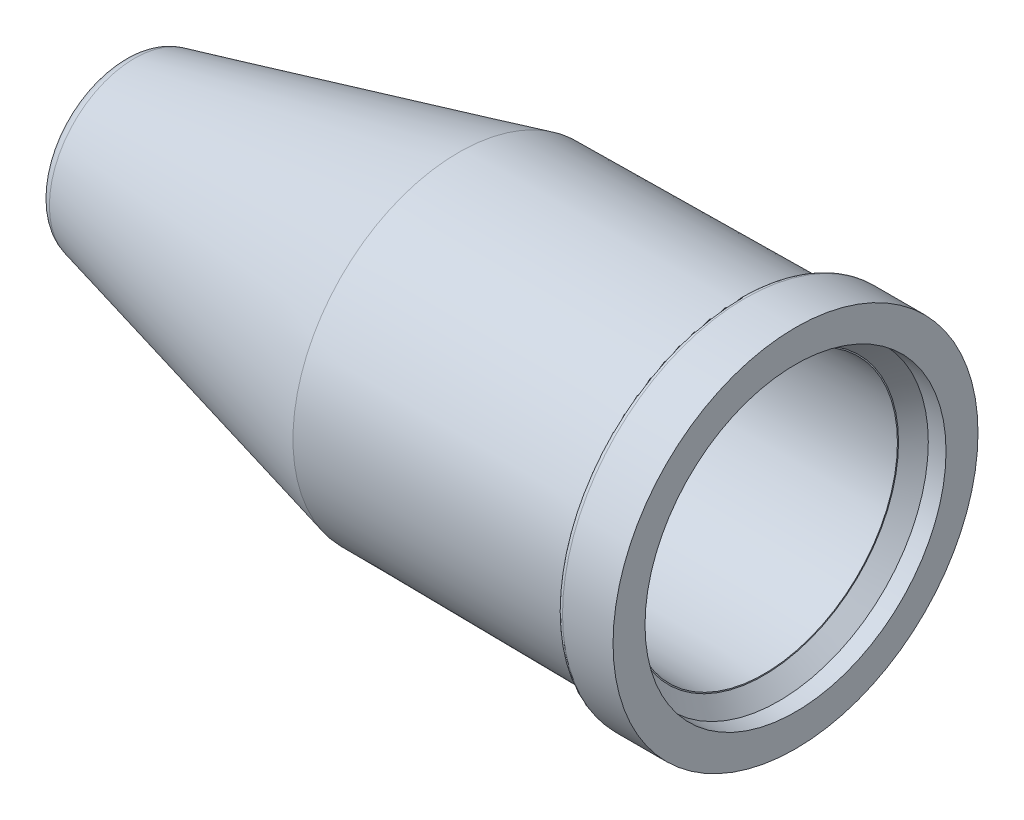
SolidWorks part; units mm, degrees
material "PBT Propósitos gerais"
ref_plane "Frontal" through (0, 0, 0) normal (0, 0, 1) x (1, 0, 0)
ref_plane "Superior" through (0, 0, 0) normal (0, 1, 0) x (1, 0, 0)
ref_plane "Lateral" through (0, 0, 0) normal (1, 0, 0) x (0, 0, -1)
sketch "Sketch1" plane through (0, 0, 0) normal (0, 0, 1) x (1, 0, 0)
  line L0 (3, 0) -> (-11, 0) construction
  line L1 (0, 2.6807) -> (0, 3.25)
  line L2 (0, 3.25) -> (-1, 3.25)
  line L3 (-1, 3.25) -> (-1, 3)
  line L4 (-1, 3) -> (-6, 2.951)
  line L5 (-6, 2.951) -> (-12, 1.46)
  line L6 (-12, 1.46) -> (-12, 1.1823) construction
  line L7 (-11.57, 0.9) -> (-7.9512, 0.8621) construction
  line L8 (-7.8522, 0.7621) -> (-7.8522, 0.4926)
  line L9 (-7.8522, 0.4926) -> (-3.5277, 0.4926)
  line L10 (-9.53, 1.475) -> (-7.28, 1.475)
  line L11 (-7.28, 1.1084) -> (-3.6842, 1.069)
  line L12 (-7.28, 1.1084) -> (-7.28, 1.25)
  line L13 (-7.28, 1.25) -> (-10.3301, 1.25) construction
  line L14 (-0.3, 2.665) -> (-0.565, 2.4)
  line L15 (-12, 1.1823) -> (-11.8522, 1.1823) construction
  line L16 (-6.81, 2.3268) -> (-0.565, 2.38)
  line L17 (-8.0717, 1.9768) -> (-10.3321, 1.35) construction
  line L18 (-10.3321, 1.35) -> (-10.3301, 1.25) construction
  line L19 (-11.8522, 1.1823) -> (-11.57, 0.9) construction
  line L20 (-6.81, 2.3268) -> (-7.5, 2.1354)
  line L21 (-0.565, 2.38) -> (-0.565, 2.4)
  line L22 (-12, 1.46) -> (-12, 1.182)
  line L23 (-0.3, 2.665) -> (0, 2.6807)
  line L24 (-2.9603, 0.8055) -> (-3.6842, 1.069)
  line L25 (-12, 1.182) -> (-11.9422, 1.182)
  line L26 (-11.9422, 1.182) -> (-11.6267, 1.1123)
  line L27 (-11.5482, 1.0147) -> (-11.5482, 0.9111)
  line L28 (-11.5482, 0.9111) -> (-7.9512, 0.8621)
  line L29 (-3.5277, 0.4926) -> (-2.9603, 0.4728)
  line L30 (-2.9603, 0.4728) -> (-2.9603, 0.8055)
  line L31 (-7.28, 1.475) -> (-7.28, 1.25)
  line L32 (-9.53, 1.475) -> (-9.53, 1.5724)
  line L33 (-9.53, 1.5724) -> (-8.0717, 1.9768)
  arc A0 (-8.0717, 1.9768) -> (-7.5, 2.1354) centre (-7.8901, 2.4319) ccw
  arc A2 (-11.6267, 1.1123) -> (-11.5482, 1.0147) centre (-11.6482, 1.0147) cw
  arc A3 (-7.8522, 0.7621) -> (-7.9512, 0.8621) centre (-7.9522, 0.7621) ccw
  point P34 (-11.5482, 1.095)
  dimension "D18" = 15.5
  dimension "D27" = 1.6679
  dimension "D31" = 3.8839
  dimension "D7" = 0.601
  dimension "D10" = 0.1
  dimension "D6" = 2.9199
  dimension "D39" = 0.1
  dimension "D37" = 0.49
  dimension "D43" = 0.3
  dimension "D44" = 2.25
  dimension "D46" = 4.8
  dimension "D47" = 5.33
  dimension "D23" = 4.6535
  dimension "D38" = 2.44
  dimension "D48" = 1.8222
  dimension "D52" = 0.1
  dimension "D1" = 6.5
  dimension "D2" = 5.902
  dimension "D3" = 6
  dimension "D4" = 1
  dimension "D5" = 3
  dimension "D8" = 5.19
  dimension "D9" = 4.1478
  dimension "D11" = 0.9852
  dimension "D12" = 1.25
  dimension "D13" = 0.628
  dimension "D14" = 6
  dimension "D15" = 4.72
  dimension "D16" = 8.3158
  dimension "D17" = 2.1379
  dimension "D19" = 2.3645
  dimension "D20" = 9.0397
  dimension "D21" = 45
  dimension "D22" = 4.76
  dimension "D24" = 2.7
  dimension "D25" = 2.2167
  dimension "D26" = 3.0501
  dimension "D28" = 12
  dimension "D29" = 45
  dimension "D30" = 4.5
  dimension "D32" = 1.8
  dimension "D33" = 1.7241
  dimension "D34" = 2.95
  dimension "D35" = 13.956
  dimension "D36" = 5.3614
  dimension "D40" = 0.565
  dimension "D41" = 20
  dimension "D45" = 0.1478
  dimension "D49" = 0.394
  dimension "D50" = 4.09
  dimension "D51" = 2.19
  dimension "D53" = 2.364
  dimension "D54" = 0.9456
  dimension "D56" = 2
revolve "Base-Revolve" add sketch "Sketch1" angle 360 about L0
fillet "Fillet1" radius 0.3 1 edges at (-12, 0, -1.46)
fillet "Fillet2" radius 0.1 1 edges at (-1, 0, -3.25)
scale "Molde (1,5%)" [suppressed]
